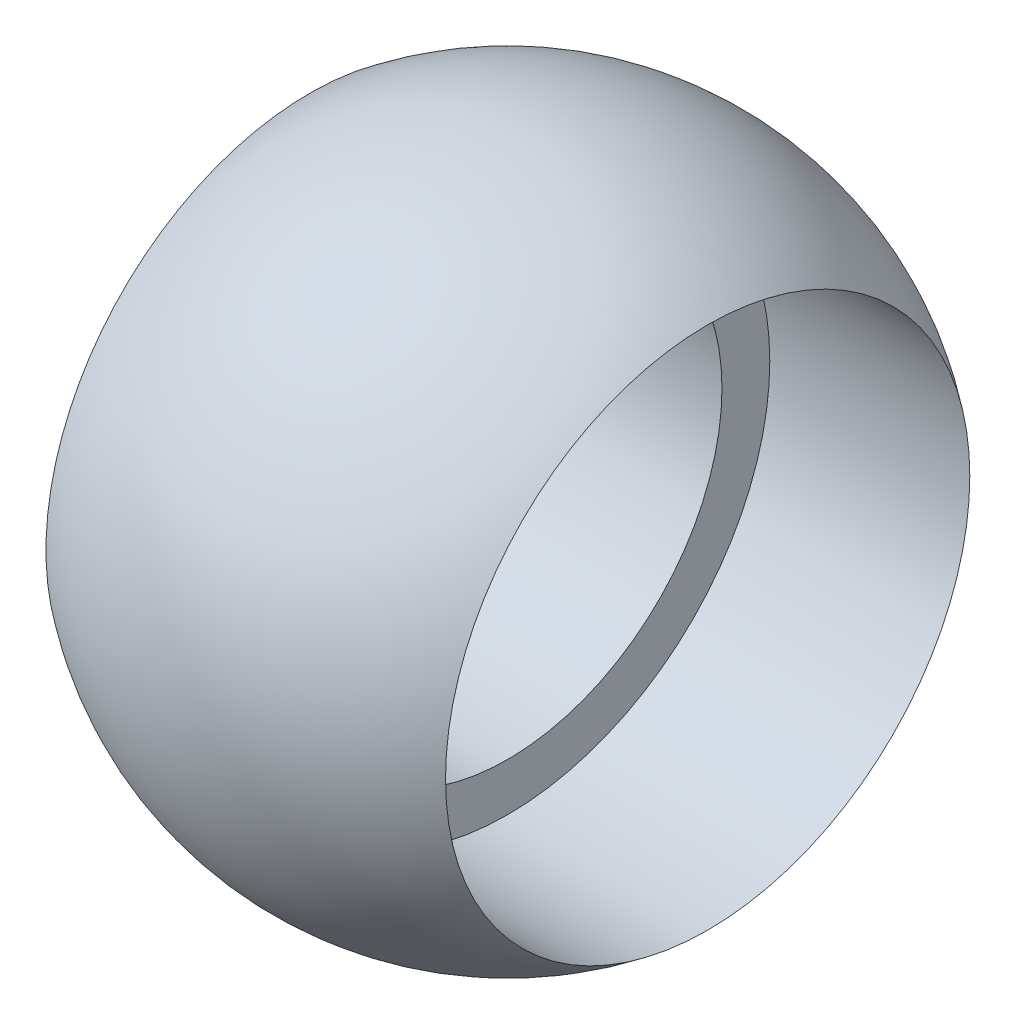
SolidWorks part; units mm, degrees
ref_plane "Front Plane" through (0, 0, 0) normal (0, 0, 1) x (1, 0, 0)
ref_plane "Top Plane" through (0, 0, 0) normal (0, 1, 0) x (1, 0, 0)
ref_plane "Right Plane" through (0, 0, 0) normal (1, 0, 0) x (0, 0, -1)
sketch "Sketch1" plane through (0, 0, 0) normal (1, 0, 0) x (0, 0, -1)
  line L1 (-20, 0) -> (20, 0)
  arc A0 (20, 0) -> (-20, 0) centre (0, 0) ccw
revolve "Revolve1" add sketch "Sketch1" angle 360 about L1
sketch "Sketch2" plane through (0, 0, 0) normal (1, 0, 0) x (0, 0, -1)
  circle A0 centre (0, 0) radius 13
extrude "Cut-Extrude2" cut sketch "Sketch2" against normal mid plane 100 from offset 0
sketch "Sketch3" plane through (0, 0, 0) normal (1, 0, 0) x (0, 0, -1)
  circle A0 centre (0, 0) radius 15.9962
extrude "Cut-Extrude3" cut sketch "Sketch3" against normal blind 25 from offset 12 contours A0 offset against normal yes
sketch "Sketch4" plane through (0, 0, 0) normal (1, 0, 0) x (0, 0, -1)
  circle A0 centre (0, 0) radius 15.9
extrude "Cut-Extrude4" cut sketch "Sketch4" along normal blind 25
